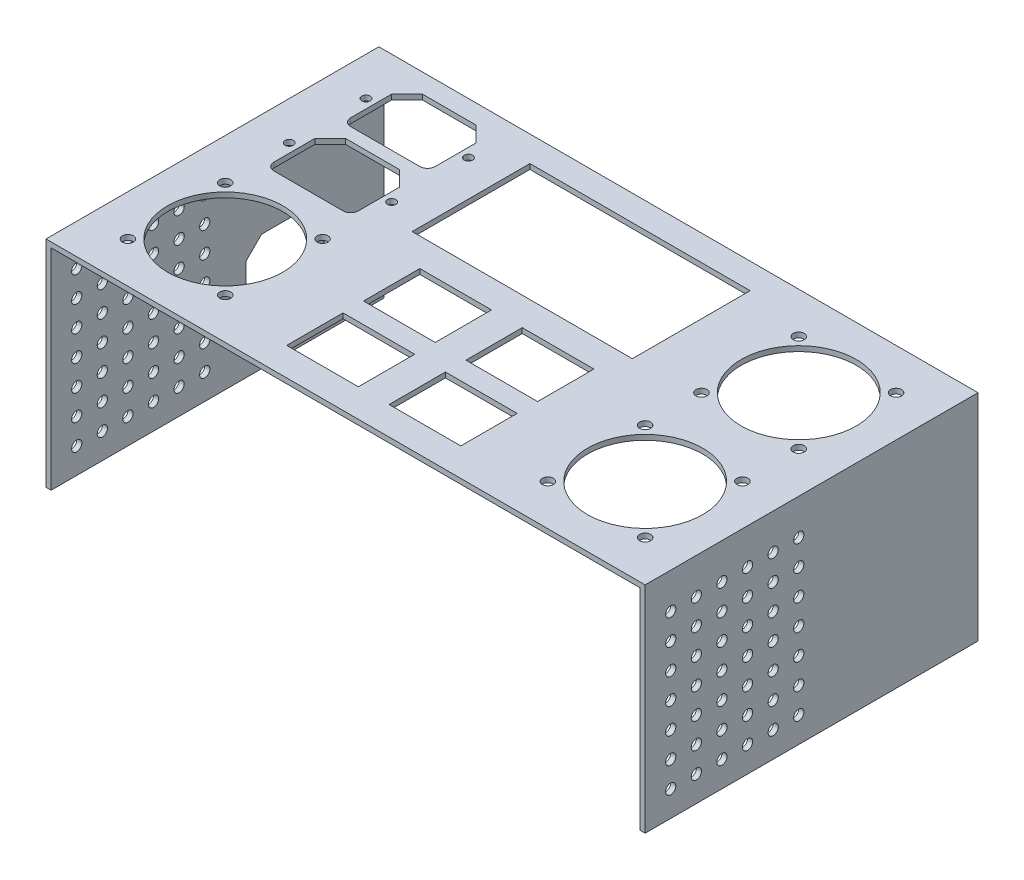
SolidWorks part; units mm, degrees
ref_plane "Спереди" through (0, 0, 0) normal (0, 0, 1) x (1, 0, 0)
ref_plane "Сверху" through (0, 0, 0) normal (0, 1, 0) x (1, 0, 0)
ref_plane "Справа" through (0, 0, 0) normal (1, 0, 0) x (0, 0, -1)
sketch "Эскиз2" plane through (0, 0, 0) normal (0, 0, 1) x (1, 0, 0)
  line L0 (2, 0) -> (2, 82)
  line L1 (0, 0) -> (234, 0) construction
  line L2 (0, 0) -> (0, 84)
  line L3 (0, 84) -> (234, 84)
  line L4 (234, 0) -> (234, 84)
  line L5 (2, 82) -> (232, 82)
  line L6 (232, 82) -> (232, 0)
  line L7 (2, 0) -> (0, 0)
  line L8 (232, 0) -> (234, 0)
  dimension "D1" = 2
  dimension "D2" = 2
  dimension "D3" = 2
  dimension "D4" = 234
  dimension "D5" = 84
extrude "Бобышка-Вытянуть1" add sketch "Эскиз2" along normal blind 130
sketch "Эскиз4" plane through (0, 84, 0) normal (0, 1, 0) x (1, 0, 0)
  line L0 (251.1453, -95) -> (-4.7569, -95) construction
  line L1 (24.5, -7.5) -> (45.5, -7.5)
  line L2 (18.5, -13.5) -> (18.5, -29.5)
  line L3 (21.5, -32.5) -> (48.5, -32.5)
  line L4 (51.5, -13.5) -> (51.5, -29.5)
  line L5 (83, -67) -> (111, -67)
  line L6 (83, -67) -> (83, -89)
  line L7 (83, -89) -> (111, -89)
  line L8 (111, -67) -> (111, -89)
  line L9 (69, -10) -> (155, -10)
  line L10 (69, -10) -> (69, -56)
  line L11 (69, -56) -> (155, -56)
  line L12 (155, -10) -> (155, -56)
  line L13 (35, -63.9719) -> (35, -137.8782) construction
  line L14 (18.5, -13.5) -> (24.5, -7.5)
  line L15 (45.5, -7.5) -> (51.5, -13.5)
  line L16 (5.7479, -20) -> (61.0313, -20) construction
  line L17 (0, -130) -> (0, 0) construction
  line L18 (234, -130) -> (0, -130) construction
  line L19 (234, 0) -> (0, 0) construction
  line L20 (18.5, -43.5) -> (24.5, -37.5)
  line L21 (21.5, -62.5) -> (48.5, -62.5)
  line L22 (18.5, -43.5) -> (18.5, -59.5)
  line L23 (51.5, -43.5) -> (51.5, -59.5)
  line L24 (45.5, -37.5) -> (51.5, -43.5)
  line L25 (24.5, -37.5) -> (45.5, -37.5)
  line L26 (123, -67) -> (151, -67)
  line L27 (151, -67) -> (151, -89)
  line L28 (123, -89) -> (151, -89)
  line L29 (123, -67) -> (123, -89)
  line L30 (123, -97) -> (151, -97)
  line L31 (151, -97) -> (151, -119)
  line L32 (123, -119) -> (151, -119)
  line L33 (123, -97) -> (123, -119)
  line L34 (83, -97) -> (111, -97)
  line L35 (111, -97) -> (111, -119)
  line L36 (83, -119) -> (111, -119)
  line L37 (83, -97) -> (83, -119)
  line L38 (117, 52.8736) -> (117, -175.7645) construction
  line L39 (234, -130) -> (234, 0) construction
  line L40 (-7.4586, -35) -> (251.1453, -35) construction
  line L41 (199, 35.814) -> (199, -190.1199) construction
  circle A0 centre (35, -95) radius 22.5
  circle A1 centre (54, -114) radius 2.15
  circle A2 centre (16, -114) radius 2.15
  circle A3 centre (16, -76) radius 2.15
  circle A4 centre (54, -76) radius 2.15
  circle A5 centre (15, -20) radius 1.65
  circle A6 centre (55, -20) radius 1.65
  circle A7 centre (15, -50) radius 1.65
  circle A8 centre (55, -50) radius 1.65
  circle A9 centre (199, -95) radius 22.5
  circle A10 centre (218, -114) radius 2.15
  circle A11 centre (180, -114) radius 2.15
  circle A12 centre (180, -76) radius 2.15
  circle A13 centre (218, -76) radius 2.15
  circle A14 centre (199, -35) radius 22.5
  circle A15 centre (218, -54) radius 2.15
  circle A16 centre (180, -54) radius 2.15
  circle A17 centre (180, -16) radius 2.15
  circle A18 centre (218, -16) radius 2.15
  arc A19 (48.5, -32.5) -> (51.5, -29.5) centre (48.5, -29.5) ccw
  arc A20 (18.5, -29.5) -> (21.5, -32.5) centre (21.5, -29.5) ccw
  arc A21 (48.5, -62.5) -> (51.5, -59.5) centre (48.5, -59.5) ccw
  arc A22 (21.5, -62.5) -> (18.5, -59.5) centre (21.5, -59.5) cw
  point P4 (18.5, -7.5)
  point P7 (51.5, -7.5)
  point P94 (51.5, -32.5)
  point P97 (18.5, -32.5)
  dimension "D3" = 19
  dimension "D4" = 19
  dimension "D5" = 4.3
  dimension "D6" = 45
  dimension "D9" = 38
  dimension "D10" = 38
  dimension "D13" = 3.3
  dimension "D37" = 3
  dimension "D38" = 3
  dimension "D7" = 86
  dimension "D8" = 46
  dimension "D11" = 33
  dimension "D12" = 25
  dimension "D14" = 35
  dimension "D17" = 35
  dimension "D18" = 40
  dimension "D19" = 3.5
  dimension "D20" = 12.5
  dimension "D21" = 20
  dimension "D22" = 16.5
  dimension "D24" = 28
  dimension "D25" = 22
  dimension "D28" = 117
  dimension "D29" = 6
  dimension "D30" = 6
  dimension "D31" = 48
  dimension "D32" = 35
  dimension "D33" = 35
  dimension "D34" = 25
  dimension "D1" = 2
  dimension "D2" = 2
  dimension "D23" = 2
  dimension "D26" = 2
  dimension "D27" = 2
  dimension "D35" = 2
  dimension "D36" = 2
extrude "Вырез-Вытянуть1" cut sketch "Эскиз4" against normal through all
sketch "Эскиз5" plane through (0, 0, 0) normal (-1, 0, 0) x (0, 0, 1)
  line L0 (40, 101.1302) -> (40, -26.6675) construction
  line L1 (-23.354, 30) -> (150.1985, 30) construction
  line L2 (130, 0) -> (0, 0) construction
  line L3 (32.2, 45.5) -> (47.8, 45.5)
  line L4 (26.2, 39.5) -> (26.2, 17.5)
  line L5 (29.2, 14.5) -> (50.8, 14.5)
  line L6 (53.8, 39.5) -> (53.8, 17.5)
  line L7 (0, 84) -> (0, 0) construction
  line L8 (26.2, 39.5) -> (32.2, 45.5)
  line L9 (47.8, 45.5) -> (53.8, 39.5)
  circle A0 centre (58, 30) radius 1.6
  circle A1 centre (22, 30) radius 1.6
  arc A2 (50.8, 14.5) -> (53.8, 17.5) centre (50.8, 17.5) ccw
  arc A3 (26.2, 17.5) -> (29.2, 14.5) centre (29.2, 17.5) ccw
  point P8 (26.2, 45.5)
  point P11 (53.8, 45.5)
  point P18 (53.8, 14.5)
  point P21 (26.2, 14.5)
  dimension "D1" = 3.2
  dimension "D2" = 18
  dimension "D3" = 36
  dimension "D10" = 3
  dimension "D4" = 27.6
  dimension "D5" = 31
  dimension "D6" = 15.5
  dimension "D7" = 30
  dimension "D8" = 40
  dimension "D9" = 13.8
extrude "Вырез-Вытянуть2" cut sketch "Эскиз5" against normal blind 10
sketch "Эскиз6" plane through (0, 0, 0) normal (-1, 0, 0) x (0, 0, 1)
  line L0 (70, 99.3803) -> (70, -19.9575) construction
  line L1 (61.6353, 10) -> (143.4482, 10) construction
  line L2 (130, 84) -> (130, 0) construction
  line L3 (130, 0) -> (0, 0) construction
  circle A0 centre (70, 10) radius 2
  circle A1 centre (80, 10) radius 2
  circle A2 centre (90, 10) radius 2
  circle A3 centre (100, 10) radius 2
  circle A4 centre (110, 10) radius 2
  circle A5 centre (120, 10) radius 2
  circle A6 centre (80, 20) radius 2
  circle A7 centre (90, 20) radius 2
  circle A8 centre (100, 20) radius 2
  circle A9 centre (110, 20) radius 2
  circle A10 centre (120, 20) radius 2
  circle A11 centre (80, 30) radius 2
  circle A12 centre (90, 30) radius 2
  circle A13 centre (100, 30) radius 2
  circle A14 centre (110, 30) radius 2
  circle A15 centre (120, 30) radius 2
  circle A16 centre (80, 40) radius 2
  circle A17 centre (90, 40) radius 2
  circle A18 centre (100, 40) radius 2
  circle A19 centre (110, 40) radius 2
  circle A20 centre (120, 40) radius 2
  circle A21 centre (80, 50) radius 2
  circle A22 centre (90, 50) radius 2
  circle A23 centre (100, 50) radius 2
  circle A24 centre (110, 50) radius 2
  circle A25 centre (120, 50) radius 2
  circle A26 centre (80, 60) radius 2
  circle A27 centre (90, 60) radius 2
  circle A28 centre (100, 60) radius 2
  circle A29 centre (110, 60) radius 2
  circle A30 centre (120, 60) radius 2
  circle A31 centre (80, 70) radius 2
  circle A32 centre (90, 70) radius 2
  circle A33 centre (100, 70) radius 2
  circle A34 centre (110, 70) radius 2
  circle A35 centre (120, 70) radius 2
  circle A36 centre (70, 20) radius 2
  circle A37 centre (70, 30) radius 2
  circle A38 centre (70, 40) radius 2
  circle A39 centre (70, 50) radius 2
  circle A40 centre (70, 60) radius 2
  circle A41 centre (70, 70) radius 2
  dimension "D3" = 4
  dimension "D1" = 60
  dimension "D2" = 10
  dimension "D4" = 6
  dimension "D5" = 7
extrude "Вырез-Вытянуть3" cut sketch "Эскиз6" against normal through all
